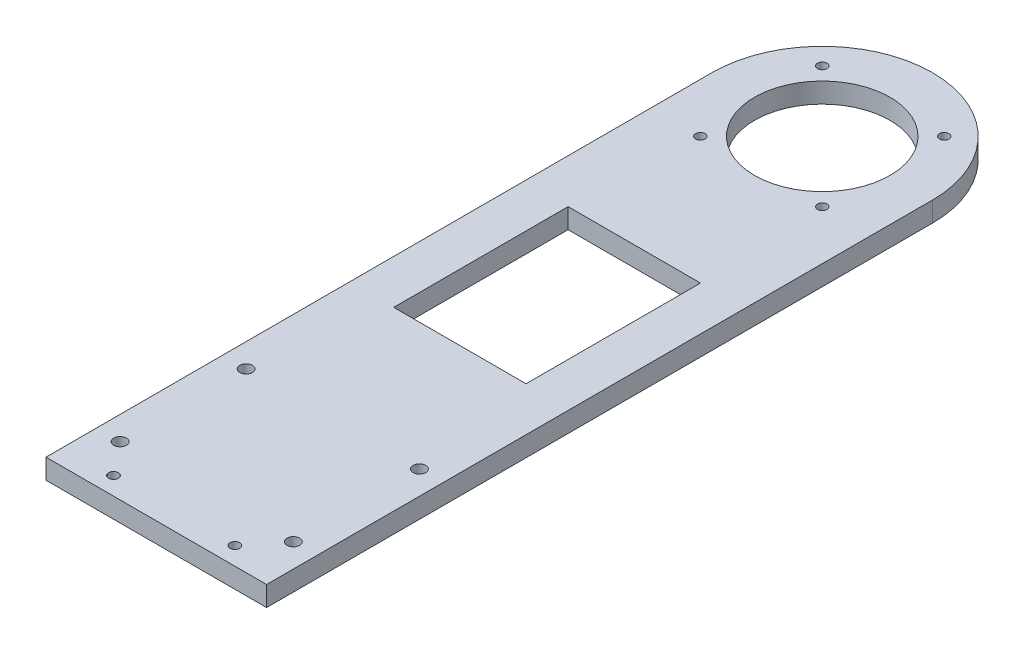
SolidWorks part; units mm, degrees
ref_plane "Front Plane" through (0, 0, 0) normal (0, 0, 1) x (1, 0, 0)
ref_plane "Top Plane" through (0, 0, 0) normal (0, 1, 0) x (1, 0, 0)
ref_plane "Right Plane" through (0, 0, 0) normal (1, 0, 0) x (0, 0, -1)
sketch "Sketch1" plane through (0, 0, 0) normal (0, 1, 0) x (1, 0, 0)
  line L0 (-35, 0) -> (-35, -211.35)
  line L1 (-35, -211.35) -> (35, -211.35)
  line L2 (35, -211.35) -> (35, 0)
  circle A0 centre (0, 0) radius 35
  point P3 (0, -211.35)
  dimension "D1" = 70
  dimension "D2" = 70
  dimension "D3" = 211.35
extrude "Boss-Extrude1" add sketch "Sketch1" along normal mid plane 6.35
sketch "Sketch2" plane through (0, 3.175, 0) normal (0, 1, 0) x (1, 0, 0)
  circle A0 centre (0, 0) radius 21.5
  dimension "D1" = 43
extrude "Cut-Extrude1" cut sketch "Sketch2" against normal through all
sketch "Sketch3" plane through (0, 3.175, 0) normal (0, 1, 0) x (1, 0, 0)
  line L1 (21, -115) -> (-21, -115)
  line L2 (21, -115) -> (21, -59.65)
  line L3 (21, -59.65) -> (-21, -59.65)
  line L4 (-21, -115) -> (-21, -59.65)
  line L5 (21, -115) -> (-21, -59.65) construction
  line L6 (21, -59.65) -> (-21, -115) construction
  line L11 (-35, -211.35) -> (35, -211.35) construction
  point P0 (0, -87.325)
  dimension "D1" = 96.35
  dimension "D2" = 42
  dimension "48" = 55.35
extrude "Cut-Extrude2" cut sketch "Sketch3" against normal through all contours L4 L1 L2 L3
sketch "Sketch4" plane through (0, -3.175, 0) normal (0, -1, 0) x (1, 0, 0)
  line L0 (19.35, 19.35) -> (-19.35, 19.35) construction
  line L1 (-19.35, 19.35) -> (-19.35, -19.35) construction
  line L2 (-19.35, -19.35) -> (19.35, -19.35) construction
  line L3 (19.35, -19.35) -> (19.35, 19.35) construction
  circle A0 centre (-19.35, 19.35) radius 1.5
  circle A1 centre (19.35, 19.35) radius 1.5
  circle A2 centre (19.35, -19.35) radius 1.5
  circle A3 centre (-19.35, -19.35) radius 1.5
  point P2 (0, 19.35)
  point P5 (-19.35, 0)
  dimension "D2" = 3
  dimension "D1" = 38.7
extrude "Cut-Extrude3" cut sketch "Sketch4" against normal through all
sketch "Sketch5" plane through (0, 3.175, 0) normal (0, 1, 0) x (1, 0, 0)
  line L0 (-35, -175.35) -> (35, -175.35) construction
  line L1 (-35, 0) -> (-35, -211.35) construction
  line L2 (35, -211.35) -> (35, 0) construction
  circle A0 centre (15, -65.35) radius 2
  circle A1 centre (-15, -65.35) radius 2
  circle A2 centre (27.5, -195.35) radius 2
  circle A3 centre (-27.5, -195.35) radius 2
  circle A4 centre (27.5, -155.35) radius 2
  circle A5 centre (-27.5, -155.35) radius 2
  dimension "D1" = 20
extrude "Cut-Extrude4" cut sketch "Sketch5" against normal through all
sketch "Sketch7" plane through (0, 3.175, 0) normal (0, 1, 0) x (1, 0, 0)
  circle A0 centre (-19.25, -205.675) radius 1.55
  circle A1 centre (19.25, -205.675) radius 1.55
  dimension "D1" = 3.1
extrude "Cut-Extrude6" cut sketch "Sketch7" against normal blind 10
